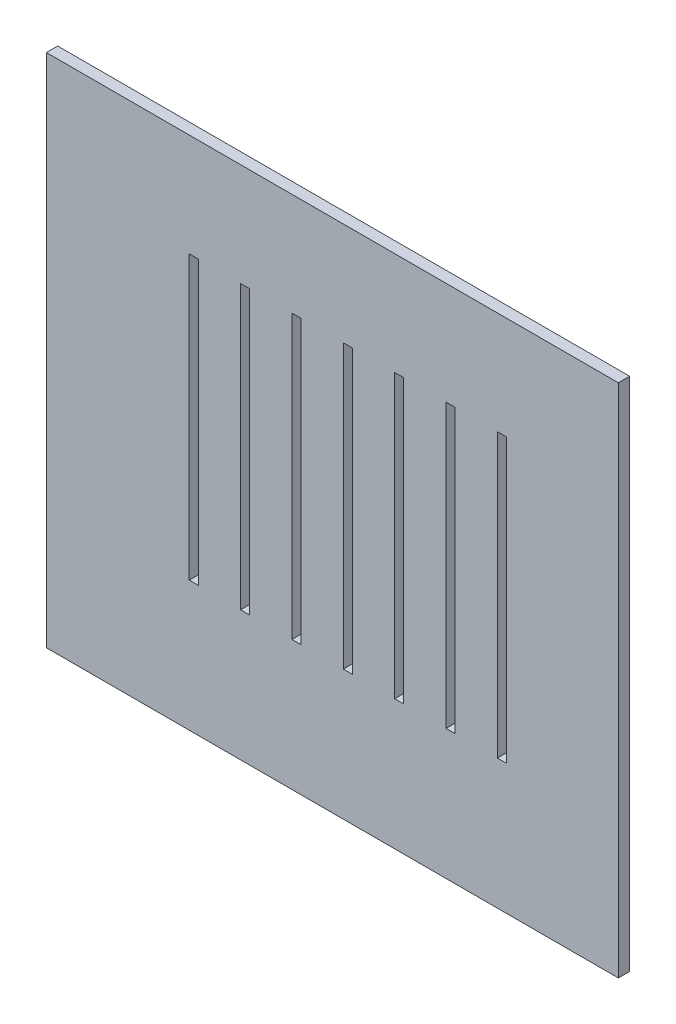
SolidWorks part; units mm, degrees
ref_plane "前视基准面" through (0, 0, 0) normal (0, 0, 1) x (1, 0, 0)
ref_plane "上视基准面" through (0, 0, 0) normal (0, 1, 0) x (1, 0, 0)
ref_plane "右视基准面" through (0, 0, 0) normal (1, 0, 0) x (0, 0, -1)
other "Configuration Table"
sketch "Sketch1" plane through (0, 0, 0) normal (0, 0, 1) x (1, 0, 0)
  line L3 (-3.9873, 5.3595) -> (94.8127, 5.3595)
  line L16 (-5.1873, 96.5595) -> (-5.1873, 5.3595)
  line L17 (-5.1873, 5.3595) -> (-3.9873, 5.3595)
  line L21 (94.8127, 5.3595) -> (96.0127, 5.3595)
  line L22 (96.0127, 5.3595) -> (96.0127, 96.5595)
  line L23 (96.0127, 96.5595) -> (-5.1873, 96.5595)
extrude "Boss-Extrude1" add sketch "Sketch1" along normal blind 2
sketch "Sketch4" plane through (0, 0, 0) normal (0, 0, -1) x (1, 0, 0)
  line L0 (-5.1873, -5.3595) -> (96.0127, -5.3595) construction
  line L1 (96.0127, -5.3595) -> (96.0127, -96.5595) construction
  line L3 (20.0938, -28.3595) -> (21.6938, -28.3595)
  line L4 (20.0938, -28.3595) -> (20.0938, -78.3595)
  line L5 (20.0938, -78.3595) -> (21.6938, -78.3595)
  line L6 (21.6938, -28.3595) -> (21.6938, -78.3595)
  line L9 (29.1803, -28.3595) -> (29.1803, -78.3595)
  line L10 (29.1803, -28.3595) -> (30.7803, -28.3595)
  line L11 (30.7803, -28.3595) -> (30.7803, -78.3595)
  line L12 (29.1803, -78.3595) -> (30.7803, -78.3595)
  line L13 (38.2668, -28.3595) -> (38.2668, -78.3595)
  line L14 (38.2668, -28.3595) -> (39.8668, -28.3595)
  line L15 (39.8668, -28.3595) -> (39.8668, -78.3595)
  line L16 (38.2668, -78.3595) -> (39.8668, -78.3595)
  line L17 (47.3532, -28.3595) -> (47.3532, -78.3595)
  line L18 (47.3532, -28.3595) -> (48.9532, -28.3595)
  line L19 (48.9532, -28.3595) -> (48.9532, -78.3595)
  line L20 (47.3532, -78.3595) -> (48.9532, -78.3595)
  line L21 (56.4397, -28.3595) -> (56.4397, -78.3595)
  line L22 (56.4397, -28.3595) -> (58.0397, -28.3595)
  line L23 (58.0397, -28.3595) -> (58.0397, -78.3595)
  line L24 (56.4397, -78.3595) -> (58.0397, -78.3595)
  line L25 (65.5262, -28.3595) -> (65.5262, -78.3595)
  line L26 (65.5262, -28.3595) -> (67.1262, -28.3595)
  line L27 (67.1262, -28.3595) -> (67.1262, -78.3595)
  line L28 (65.5262, -78.3595) -> (67.1262, -78.3595)
  line L29 (74.6127, -28.3595) -> (74.6127, -78.3595)
  line L30 (74.6127, -28.3595) -> (76.2127, -28.3595)
  line L31 (76.2127, -28.3595) -> (76.2127, -78.3595)
  line L32 (74.6127, -78.3595) -> (76.2127, -78.3595)
  dimension "D1" = 1.6
  dimension "D2" = 50
  dimension "D3" = 23
  dimension "D4" = 19.8
  dimension "D5" = 7
extrude "Cut-Extrude1" cut sketch "Sketch4" against normal blind 10
